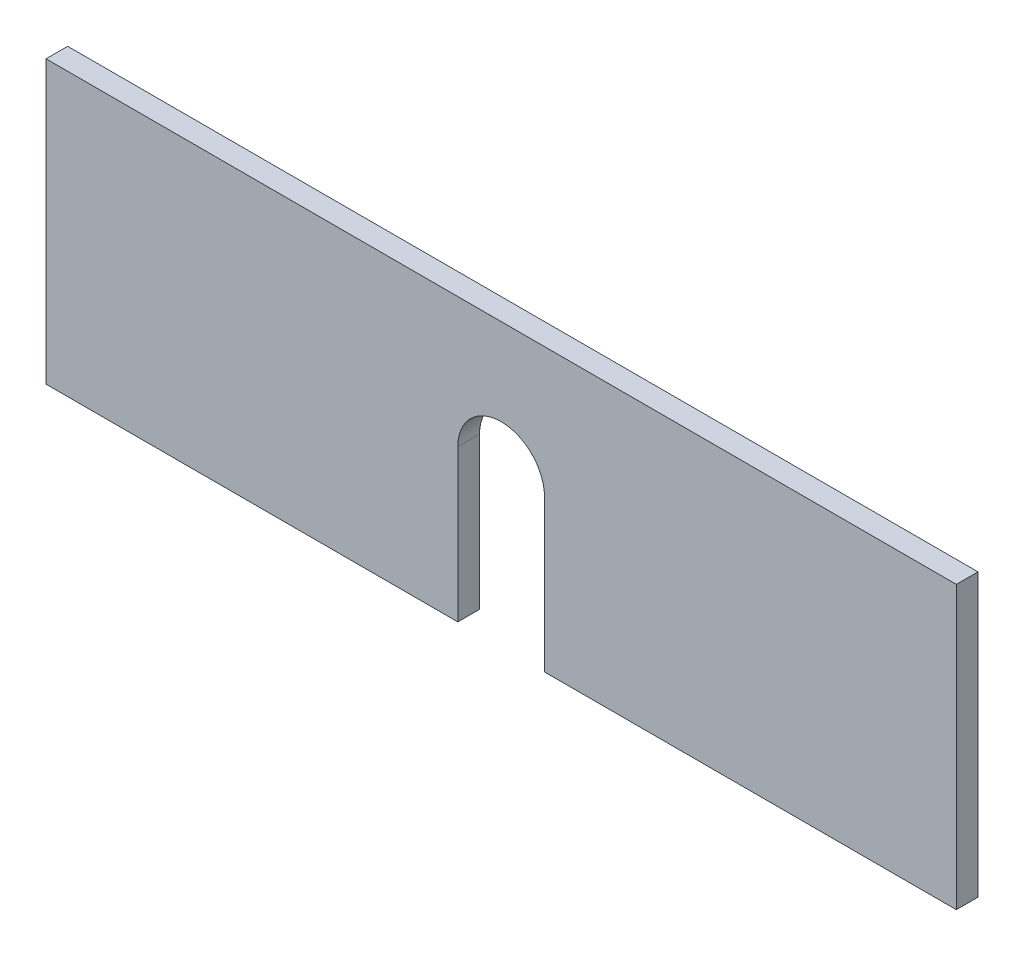
SolidWorks part; units mm, degrees
ref_plane "Front Plane" through (0, 0, 0) normal (0, 0, 1) x (1, 0, 0)
ref_plane "Top Plane" through (0, 0, 0) normal (0, 1, 0) x (1, 0, 0)
ref_plane "Right Plane" through (0, 0, 0) normal (1, 0, 0) x (0, 0, -1)
sketch "Sketch1" plane through (0, 0, 0) normal (0, 0, 1) x (1, 0, 0)
  line L0 (-43.0478, 2.7689) -> (-43.0478, -32.2311)
  line L1 (-138.0478, 32.7689) -> (71.9522, 32.7689)
  line L2 (-138.0478, 32.7689) -> (-138.0478, -32.2311)
  line L3 (-138.0478, -32.2311) -> (-43.0478, -32.2311)
  line L4 (71.9522, 32.7689) -> (71.9522, -32.2311)
  line L5 (-23.0478, 2.7689) -> (-23.0478, -32.2311)
  line L6 (-23.0478, -32.2311) -> (71.9522, -32.2311)
  arc A0 (-23.0478, 2.7689) -> (-43.0478, 2.7689) centre (-33.0478, 2.7689) ccw
  dimension "D5" = 10
  dimension "D1" = 210
  dimension "D2" = 65
  dimension "D3" = 105
  dimension "D4" = 35
extrude "Boss-Extrude1" add sketch "Sketch1" along normal blind 5
